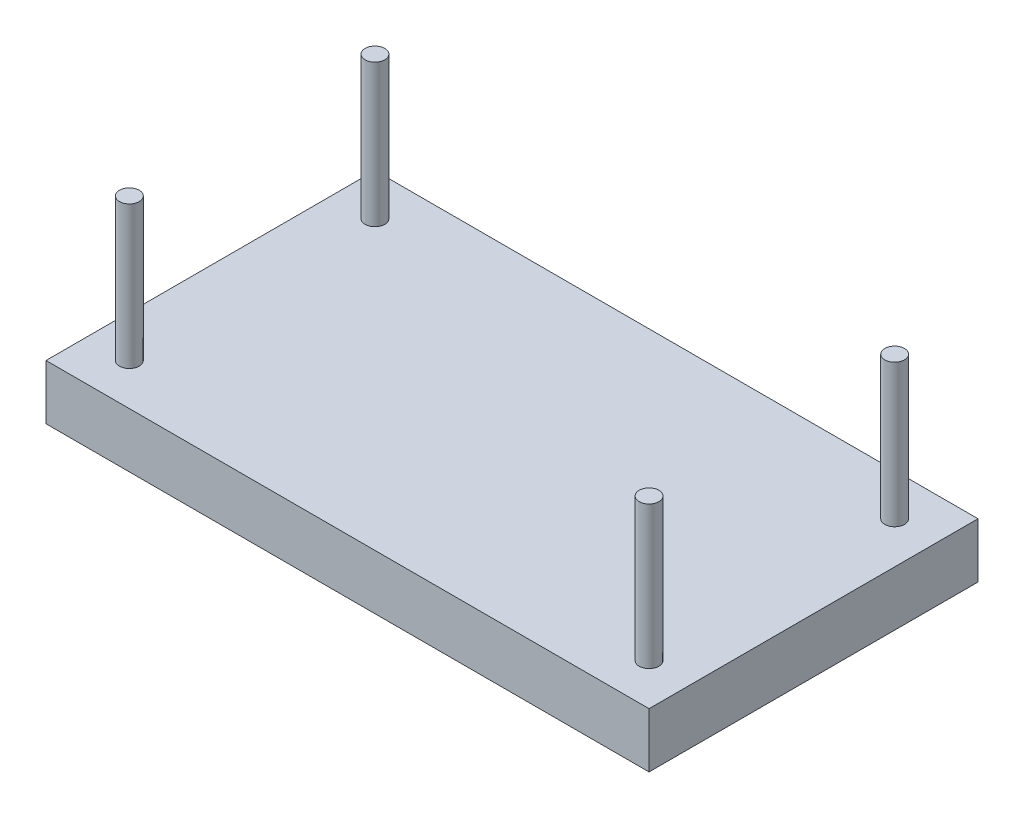
SolidWorks part; units mm, degrees
ref_plane "Front Plane" through (0, 0, 0) normal (0, 0, 1) x (1, 0, 0)
ref_plane "Top Plane" through (0, 0, 0) normal (0, 1, 0) x (1, 0, 0)
ref_plane "Right Plane" through (0, 0, 0) normal (1, 0, 0) x (0, 0, -1)
sketch "Sketch1" plane through (0, 0, 0) normal (0, 1, 0) x (1, 0, 0)
  line L0 (-2, -2) -> (-2, 28)
  line L1 (0, 0) -> (51, 0) construction
  line L2 (0, 0) -> (0, 26) construction
  line L3 (0, 26) -> (51, 26) construction
  line L4 (51, 0) -> (51, 26) construction
  line L5 (-2, 28) -> (53, 28)
  line L6 (53, -2) -> (53, 28)
  line L7 (-2, -2) -> (53, -2)
  line L8 (25.5, 28) -> (25.5, -2) construction
  line L9 (-2, 13) -> (53, 13) construction
  circle A0 centre (1.25, 1.25) radius 0.75 construction
  circle A1 centre (1.25, 24.75) radius 0.75 construction
  circle A2 centre (49.75, 24.75) radius 0.75 construction
  circle A3 centre (49.75, 1.25) radius 0.75 construction
  dimension "D4" = 1.5
  dimension "D1" = 51
  dimension "D2" = 26
  dimension "D5" = 1.25
  dimension "D6" = 1.25
  dimension "D3" = 2
extrude "Boss-Extrude1" add sketch "Sketch1" along normal blind 5
sketch "Sketch2" plane through (0, 5, 0) normal (0, 1, 0) x (1, 0, 0)
  line L0 (0, 13) -> (51, 13) construction
  line L1 (25.5, 26) -> (25.5, 0) construction
  line L8 (0, 26) -> (0, 0)
  line L9 (51, 26) -> (0, 26)
  line L10 (51, 0) -> (51, 26)
  line L11 (0, 0) -> (51, 0)
  line L12 (0, 26) -> (0, 0) construction
  line L13 (51, 26) -> (0, 26) construction
  line L14 (51, 0) -> (51, 26) construction
  line L15 (0, 0) -> (51, 0) construction
  circle A0 centre (1.8, 24.2) radius 0.9
  circle A1 centre (49.2, 24.2) radius 0.9
  circle A2 centre (49.2, 1.8) radius 0.9
  circle A3 centre (1.8, 1.8) radius 0.9
  dimension "D2" = 1.8
  dimension "D3" = 1.8
  dimension "D4" = 1.8
  dimension "D1" = 2
extrude "Boss-Extrude2" add sketch "Sketch2" along normal blind 13
